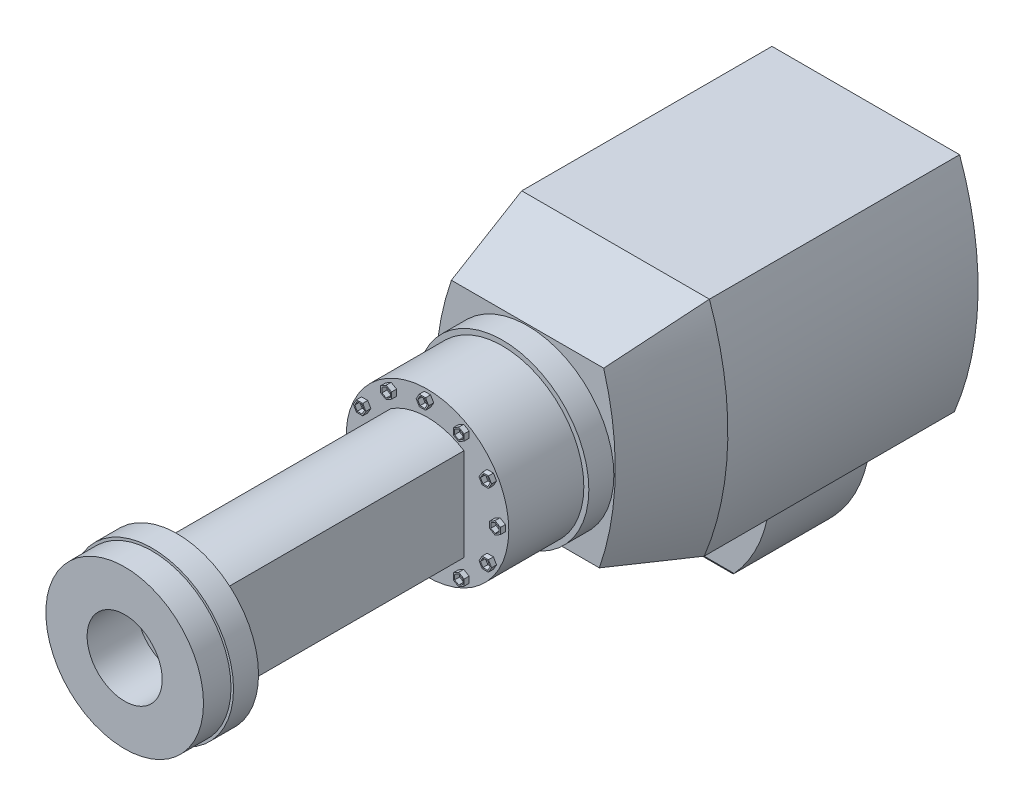
SolidWorks part; units mm, degrees
material "AISI 1045 Steel, cold drawn"
ref_plane "Front Plane" through (0, 0, 0) normal (0, 0, 1) x (1, 0, 0)
ref_plane "Top Plane" through (0, 0, 0) normal (0, 1, 0) x (1, 0, 0)
ref_plane "Right Plane" through (0, 0, 0) normal (1, 0, 0) x (0, 0, -1)
sketch "Sketch1" plane through (0, 0, 0) normal (0, 0, 1) x (1, 0, 0)
  line L0 (0, -45) -> (0, 45) construction
  line L1 (-28.4007, 45) -> (46.5993, 45)
  line L2 (-30.486, -45) -> (44.514, -45)
  arc A0 (-28.4007, 45) -> (-30.486, -45) centre (87.1397, -2.7012) ccw
  arc A1 (46.5993, 45) -> (44.514, -45) centre (-71.0265, 2.7012) cw
  point P4 (0, 0)
  point P6 (0, 0)
  dimension "D3" = 125
  dimension "D4" = 125
  dimension "D1" = 75
  dimension "D2" = 90
  dimension "D5" = 75
extrude "Boss-Extrude1" add sketch "Sketch1" along normal blind 100
ref_plane "Plane1" through (0, 0, 135) normal (0, 0, 1) x (1, 0, 0)
sketch "Sketch3" plane through (0, 0, 135) normal (0, 0, 1) x (1, 0, 0)
  line L1 (-30.486, -45) -> (44.514, -45) construction
  line L2 (46.5993, 45) -> (-28.4007, 45) construction
  line L3 (-30.486, -45) -> (44.514, -45)
  line L4 (46.5993, 45) -> (-28.4007, 45)
  line L5 (-23.2314, -35) -> (37.618, -35)
  line L6 (39.3447, 35) -> (-21.5047, 35)
  arc A0 (44.514, -45) -> (46.5993, 45) centre (-71.0265, 2.7012) ccw construction
  arc A1 (-28.4007, 45) -> (-30.486, -45) centre (87.1397, -2.7012) ccw construction
  arc A2 (44.514, -45) -> (46.5993, 45) centre (-71.0265, 2.7012) ccw
  arc A3 (-28.4007, 45) -> (-30.486, -45) centre (87.1397, -2.7012) ccw
  arc A4 (-21.5047, 35) -> (-23.2314, -35) centre (87.1397, -2.7012) ccw
  arc A5 (37.618, -35) -> (39.3447, 35) centre (-71.0265, 2.7012) ccw
  dimension "D1" = 10
loft "Loft2" add section "Sketch3" section face at (8.0566, 0, 100)
sketch "Sketch5" plane through (0, 0, 135) normal (0, 0, 1) x (1, 0, 0)
  circle A0 centre (8.92, 0) radius 34.5
  dimension "D1" = 69
extrude "Boss-Extrude2" add sketch "Sketch5" along normal blind 10
sketch "Sketch6" plane through (0, 0, 145) normal (0, 0, 1) x (1, 0, 0)
  circle A2 centre (8.92, 0) radius 32.5
  circle A3 centre (8.92, 0) radius 32.5
  dimension "D1" = 2
extrude "Boss-Extrude3" add sketch "Sketch6" along normal blind 30
sketch "Sketch7" plane through (0, 0, 175) normal (0, 0, 1) x (1, 0, 0)
  line L0 (8.92, 0) -> (37.92, 0) construction
  line L1 (39.5839, 0.9633) -> (37.9177, 1.9226)
  line L2 (37.9171, 2.5) -> (35.7535, 1.2475)
  line L3 (35.7535, 1.2475) -> (35.7564, -1.2525)
  line L4 (35.7564, -1.2525) -> (37.9229, -2.5)
  line L5 (37.9229, -2.5) -> (40.0865, -1.2475)
  line L6 (40.0865, -1.2475) -> (40.0836, 1.2525)
  line L7 (40.0836, 1.2525) -> (37.9171, 2.5)
  line L8 (37.9177, 1.9226) -> (36.2538, 0.9594)
  line L9 (36.2538, 0.9594) -> (36.256, -0.9633)
  line L10 (36.256, -0.9633) -> (37.9222, -1.9226)
  line L11 (37.9222, -1.9226) -> (39.5862, -0.9594)
  line L12 (39.5862, -0.9594) -> (39.5839, 0.9633)
  circle A0 centre (37.92, 0) radius 2.1651 construction
  dimension "D1" = 29
  dimension "D2" = 5
  dimension "D3" = 0.5
extrude "Boss-Extrude4" add sketch "Sketch7" along normal blind 2
pattern_circular "CirPattern1" count 12 over 360 about axis through (8.92, 0, 0) along (0, 0, 1) of "Boss-Extrude4"
sketch "Sketch8" plane through (0, 0, 175) normal (0, 0, 1) x (1, 0, 0)
  line L0 (8.92, 0) -> (23.5043, 0) construction
  line L1 (8.92, 22.5229) -> (8.92, -17.1744) construction
  line L2 (23.5043, 18.5) -> (23.5043, -18.5)
  line L3 (-5.6644, 18.5) -> (-5.6644, -18.5)
  arc A0 (-5.6644, 18.5) -> (23.5043, 18.5) centre (8.92, -4.2222) cw
  arc A1 (-5.6644, -18.5) -> (23.5043, -18.5) centre (8.92, 4.2222) ccw
  dimension "D2" = 27
  dimension "D1" = 37
extrude "Boss-Extrude5" add sketch "Sketch8" along normal blind 100
sketch "Sketch9" plane through (0, 0, 275) normal (0, 0, 1) x (1, 0, 0)
  circle A0 centre (8.92, 0) radius 32.5 construction
  circle A1 centre (8.92, 0) radius 32.5
extrude "Boss-Extrude6" add sketch "Sketch9" along normal blind 10
sketch "Sketch10" plane through (0, 0, 285) normal (0, 0, 1) x (1, 0, 0)
  circle A2 centre (8.92, 0) radius 31.5
  circle A3 centre (8.92, 0) radius 31.5
  dimension "D1" = 1
extrude "Boss-Extrude7" add sketch "Sketch10" along normal blind 1
sketch "Sketch11" plane through (0, 0, 286) normal (0, 0, 1) x (1, 0, 0)
  circle A1 centre (8.92, 0) radius 31.5
  circle A2 centre (8.92, 0) radius 31.5
  dimension "D1" = 0
extrude "Boss-Extrude8" add sketch "Sketch11" along normal blind 10
ref_plane "Plane2" through (-35, 0, 0) normal (1, 0, 0) x (0, 0, -1)
sketch "Sketch12" plane through (-35, 0, 0) normal (1, 0, 0) x (0, 0, -1)
  line L0 (-100, -45) -> (0, -45) construction
  circle A0 centre (-50, -45) radius 42.5
  dimension "D1" = 85
extrude "Boss-Extrude9" add sketch "Sketch12" against normal mid plane 21
sketch "Sketch13" plane through (-24.5, 0, 0) normal (1, 0, 0) x (0, 0, -1)
  line L0 (-50, -45) -> (-50, -75) construction
  line L1 (-100, -45) -> (0, -45) construction
  line L2 (-70, -45) -> (-70, -75)
  line L3 (-30, -45) -> (-30, -75)
  line L4 (-70, -45) -> (-30, -45)
  arc A0 (-70, -75) -> (-30, -75) centre (-50, -60) ccw
  dimension "D4" = 25
  dimension "D1" = 30
  dimension "D2" = 20
  dimension "D3" = 20
extrude "Boss-Extrude10" add sketch "Sketch13" along normal blind 35
ref_plane "Plane3" through (0, 0, 50) normal (0, 0, -1) x (-1, 0, 0)
sketch "Sketch14" plane through (0, 0, 50) normal (0, 0, -1) x (-1, 0, 0)
  line L3 (-10.5, -45) -> (-10.5, -87)
  line L4 (-10.5, -45) -> (-40.5, -45)
  line L5 (30.486, -45) -> (-44.514, -45) construction
  arc A1 (-40.5, -45) -> (-10.5, -87) centre (14.0227, -37.7695) ccw
  dimension "D3" = 42
  dimension "D1" = 55
  dimension "D2" = 30
extrude "Boss-Extrude12" add sketch "Sketch14" along normal mid plane 40
sketch "Sketch15" plane through (10.5, 0, 0) normal (-1, 0, 0) x (0, 0, 1)
  line L3 (70, -87) -> (70, -75)
  line L4 (30, -75) -> (30, -87)
  line L5 (30, -87) -> (70, -87)
  line L6 (70, -87) -> (70, -75)
  line L7 (30, -75) -> (30, -87)
  line L8 (30, -87) -> (70, -87)
  arc A1 (30, -75) -> (70, -75) centre (50, -60) ccw
  arc A2 (30, -75) -> (70, -75) centre (50, -60) ccw
  dimension "D1" = 0
extrude "Cut-Extrude1" cut sketch "Sketch15" against normal blind 40
sketch "Sketch16" plane through (0, 0, 296) normal (0, 0, 1) x (1, 0, 0)
  circle A0 centre (8.92, 0) radius 15
  dimension "D1" = 30
extrude "Cut-Extrude2" cut sketch "Sketch16" against normal blind 20
sketch "Sketch17" plane through (-45.5, 0, 0) normal (-1, 0, 0) x (0, 0, 1)
  circle A0 centre (50, -45) radius 15
  dimension "D1" = 30
extrude "Cut-Extrude3" cut sketch "Sketch17" against normal blind 20
